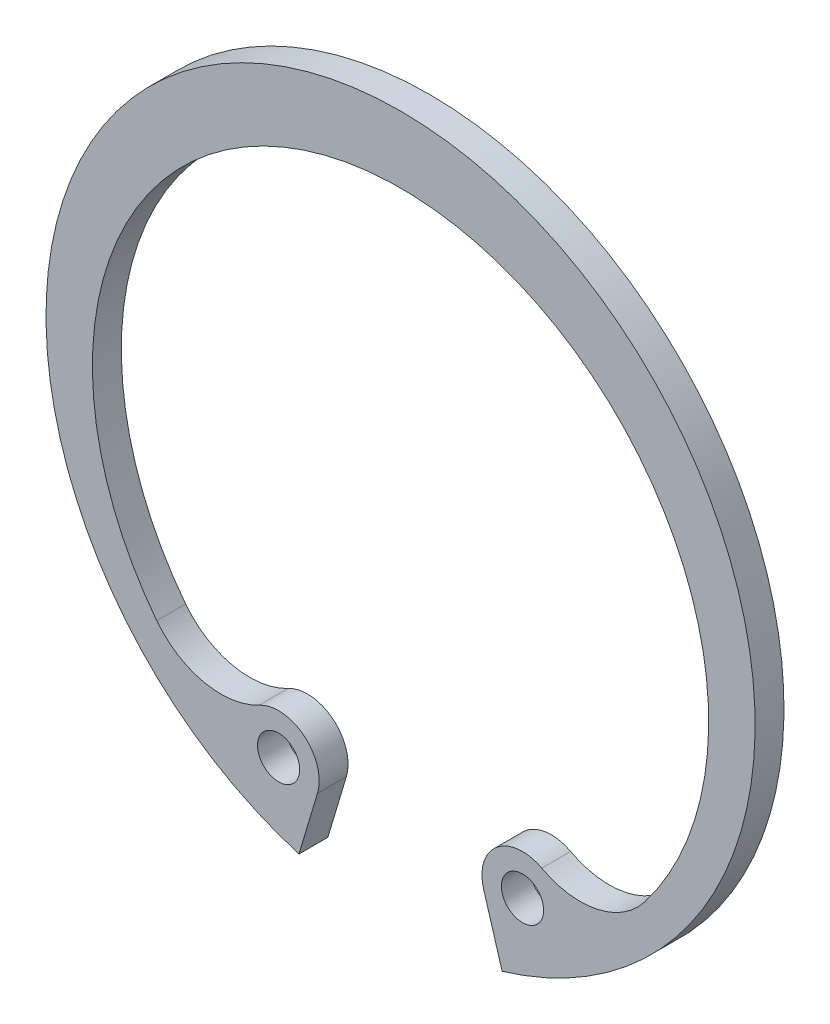
SolidWorks part; units mm, degrees
material "SPRING STEEL ASTM A 229"
ref_plane "Front Plane" through (0, 0, 0) normal (0, 0, 1) x (1, 0, 0)
ref_plane "Top Plane" through (0, 0, 0) normal (0, 1, 0) x (1, 0, 0)
ref_plane "Right Plane" through (0, 0, 0) normal (1, 0, 0) x (0, 0, -1)
sketch "Sketch1" plane through (0, 0, 0) normal (0, 0, 1) x (1, 0, 0)
  line L0 (-1.5431, 0) -> (1.5431, 0) construction
  line L1 (0, 0) -> (0, 12.95) construction
  line L2 (4.5689, -15.2816) -> (3.7376, -12.5012)
  line L3 (-4.5689, -15.2816) -> (-3.7376, -12.5012)
  line L4 (0, 0) -> (11.9398, -10.5756) construction
  line L5 (0, 0) -> (-11.9398, -10.5756) construction
  line L6 (-5.214, -11.0682) -> (-5.7583, -12.8886) construction
  line L7 (5.2712, -11.2593) -> (5.7012, -12.6976) construction
  arc A0 (-3.7376, -12.5012) -> (-6.3508, -10.3713) centre (-5.4862, -11.9784) ccw
  arc A1 (6.3508, -10.3713) -> (3.7376, -12.5012) centre (5.4862, -11.9784) ccw
  arc A2 (10.817, -9.581) -> (-10.817, -9.581) centre (0, -0.9121) ccw construction
  arc A3 (4.5689, -15.2816) -> (-4.5689, -15.2816) centre (0, 0) ccw
  circle A4 centre (5.4862, -11.9784) radius 0.95
  circle A5 centre (-5.4862, -11.9784) radius 0.95
  arc A7 (10.9681, -9.3889) -> (-10.9681, -9.3889) centre (0, -0.9121) ccw
  arc A8 (-5.4862, -11.9784) -> (5.4862, -11.9784) centre (0, 0) ccw construction
  arc A9 (-10.9681, -9.3889) -> (-6.3508, -10.3713) centre (-8.0801, -7.1569) ccw
  arc A10 (6.3508, -10.3713) -> (10.9681, -9.3889) centre (8.0801, -7.1569) ccw
  dimension "GrooveDia" = 31.9
  dimension "TipRad" = 1.825
  dimension "HoleOffsetRad" = 13.175
  dimension "HoleDia" = 1.9
  dimension "FilletRad" = 3.65
  dimension "LargeRad" = 12.95
  dimension "SmallRad" = 14.45
  dimension "SmallAngle" = 96.935
  dimension "GapAngle" = 33.292
extrude "Body" add sketch "Sketch1" against normal blind 1.3
